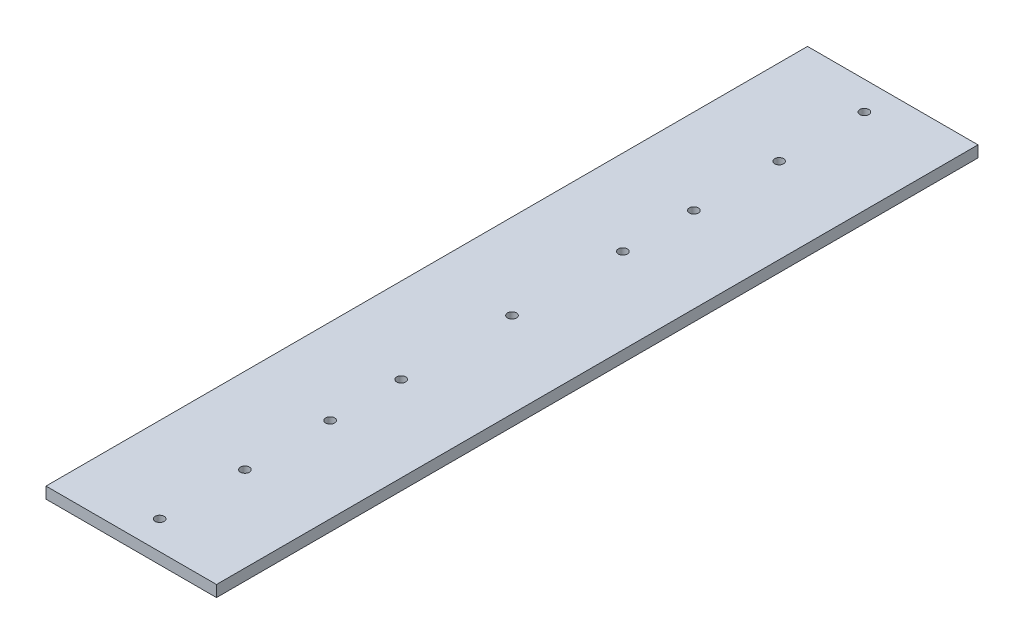
SolidWorks part; units mm, degrees
ref_plane "Front Plane" through (0, 0, 0) normal (0, 0, 1) x (1, 0, 0)
ref_plane "Top Plane" through (0, 0, 0) normal (0, 1, 0) x (1, 0, 0)
ref_plane "Right Plane" through (0, 0, 0) normal (1, 0, 0) x (0, 0, -1)
sketch "Sketch2" plane through (0, 0, 0) normal (0, 1, 0) x (1, 0, 0)
  line L1 (-125.4545, 227.7727) -> (-65.4545, 227.7727)
  line L2 (-125.4545, 227.7727) -> (-125.4545, -40.2273)
  line L3 (-125.4545, -40.2273) -> (-65.4545, -40.2273)
  line L4 (-65.4545, 227.7727) -> (-65.4545, -40.2273)
  circle A0 centre (-95.4545, 217.7727) radius 1.58
  circle A1 centre (-95.4545, 187.7727) radius 1.58
  circle A2 centre (-95.4545, 157.7727) radius 1.58
  circle A3 centre (-95.4545, 132.7727) radius 1.58
  circle A4 centre (-95.4545, 93.7727) radius 1.58
  circle A5 centre (-95.4545, 54.7727) radius 1.58
  circle A6 centre (-95.4545, 29.7727) radius 1.58
  circle A7 centre (-95.4545, -0.2273) radius 1.58
  circle A8 centre (-95.4545, -30.2273) radius 1.58
  point P0 (-95.4545, 93.7727)
  dimension "D3" = 3.16
  dimension "D5" = 3.16
  dimension "D7" = 3.16
  dimension "D9" = 3.16
  dimension "D11" = 3.16
  dimension "D13" = 3.16
  dimension "D15" = 3.16
  dimension "D17" = 3.16
  dimension "D20" = 3.16
  dimension "D1" = 268
  dimension "D2" = 60
  dimension "D4" = 10
  dimension "D6" = 40
  dimension "D8" = 70
  dimension "D10" = 95
  dimension "D12" = 134
  dimension "D14" = 95
  dimension "D16" = 70
  dimension "D18" = 40
  dimension "D19" = 10
extrude "Boss-Extrude1" add sketch "Sketch2" along normal blind 4
